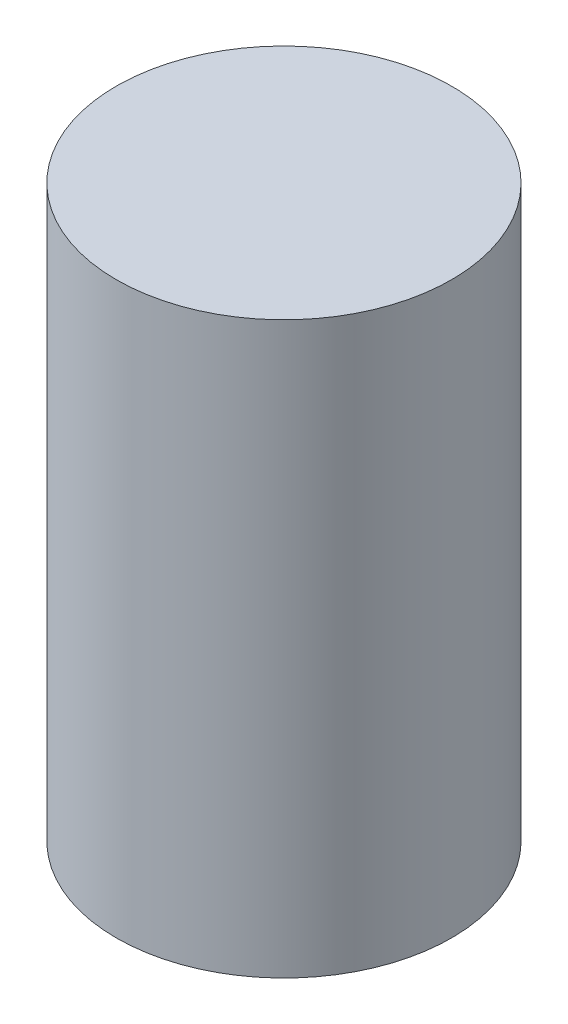
SolidWorks part; units mm, degrees
ref_plane "Front Plane" through (0, 0, 0) normal (0, 0, 1) x (1, 0, 0)
ref_plane "Top Plane" through (0, 0, 0) normal (0, 1, 0) x (1, 0, 0)
ref_plane "Right Plane" through (0, 0, 0) normal (1, 0, 0) x (0, 0, -1)
sketch "Sketch1" plane through (0, 0, 0) normal (0, 1, 0) x (1, 0, 0)
  circle A0 centre (0, 0) radius 2
  dimension "D1" = 4
extrude "Boss-Extrude1" add sketch "Sketch1" along normal blind 6.8
